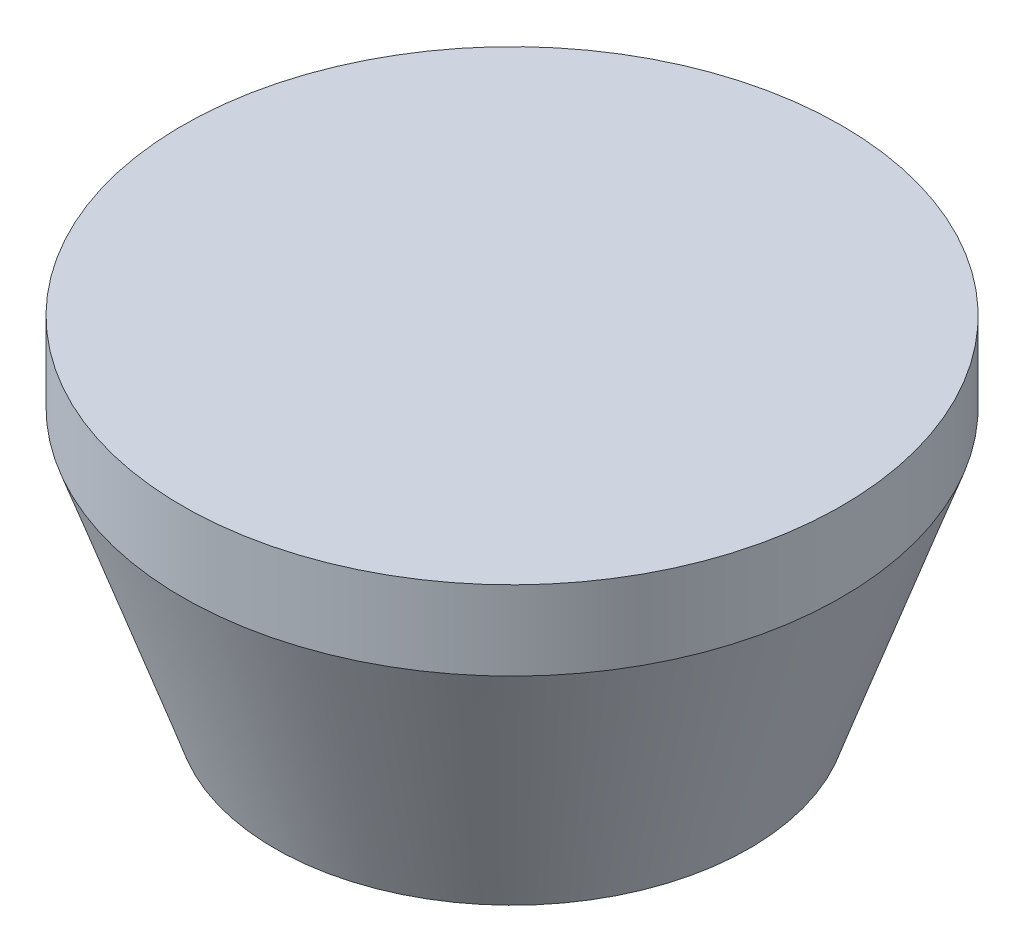
SolidWorks part; units mm, degrees
ref_plane "Front Plane" through (0, 0, 0) normal (0, 0, 1) x (1, 0, 0)
ref_plane "Top Plane" through (0, 0, 0) normal (0, 1, 0) x (1, 0, 0)
ref_plane "Right Plane" through (0, 0, 0) normal (1, 0, 0) x (0, 0, -1)
sketch "Sketch1" plane through (0, 0, 0) normal (0, 0, 1) x (1, 0, 0)
  line L0 (0, 0) -> (12.5, 0)
  line L1 (12.5, 0) -> (12.5, -3)
  line L2 (12.5, -3) -> (9, -13)
  line L3 (9, -13) -> (5.6569, -13)
  line L4 (0, -5) -> (0, 0)
  arc A0 (4.714, -11.6667) -> (0, -5) centre (0, -10) ccw
  arc A1 (4.714, -11.6667) -> (5.6569, -13) centre (5.6569, -12) ccw
  point P8 (0, 0)
  dimension "D5" = 10
  dimension "D2" = 1
  dimension "D1" = 12.5
  dimension "D3" = 13
  dimension "D4" = 3
  dimension "D6" = 3
  dimension "D7" = 9
revolve "Revolve1" add sketch "Sketch1" angle 360 about L4
